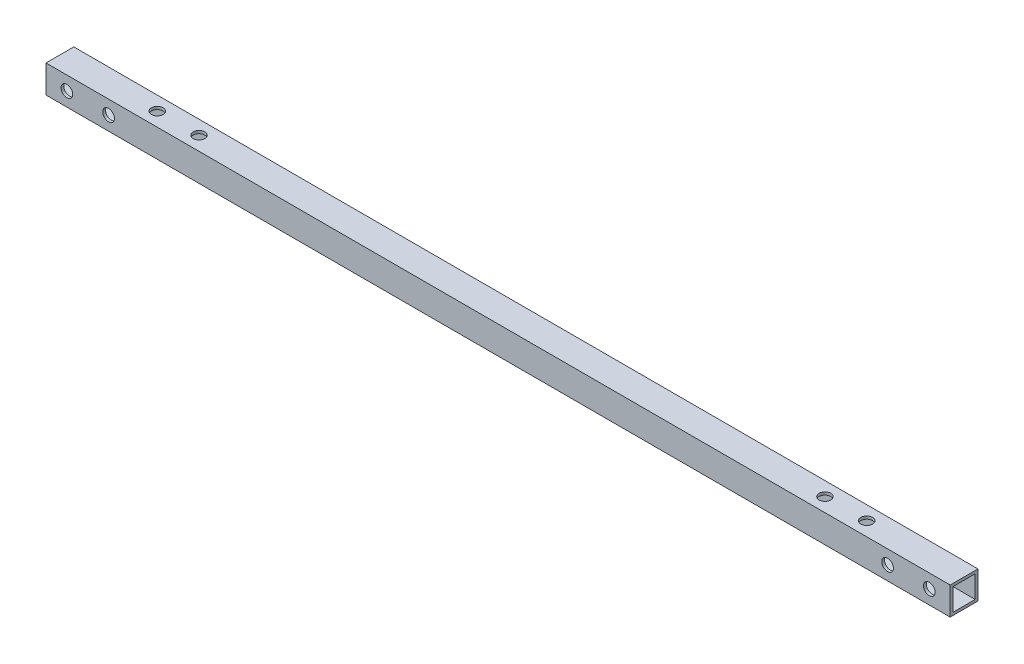
SolidWorks part; units mm, degrees
material "5052-H34"
ref_plane "正面" through (0, 0, 0) normal (0, 0, 1) x (1, 0, 0)
ref_plane "平面" through (0, 0, 0) normal (0, 1, 0) x (1, 0, 0)
ref_plane "右側面" through (0, 0, 0) normal (1, 0, 0) x (0, 0, -1)
sketch "ｽｹｯﾁ1" plane through (0, 0, 0) normal (1, 0, 0) x (0, 0, -1)
  line L1 (-5, 5) -> (5, 5)
  line L2 (-5, 5) -> (-5, -5)
  line L3 (-5, -5) -> (5, -5)
  line L4 (5, 5) -> (5, -5)
  line L5 (-5, 5) -> (5, -5) construction
  line L6 (-5, -5) -> (5, 5) construction
  point P0 (0, 0)
  dimension "D1" = 10
extrude "押し出し-薄板1" add sketch "ｽｹｯﾁ1" along normal blind 325 thin
sketch "ｽｹｯﾁ2" plane through (0, 0, 5) normal (0, 0, 1) x (1, 0, 0)
  line L0 (162.5, 5) -> (162.5, -5) construction
  line L1 (325, 5) -> (0, 5) construction
  line L2 (325, -5) -> (0, -5) construction
  line L3 (0, 0) -> (22.5, 0) construction
  circle A0 centre (22.5, 0) radius 2.1
  circle A1 centre (7.5, 0) radius 2.1
  circle A2 centre (317.5, 0) radius 2.1
  circle A3 centre (302.5, 0) radius 2.1
  dimension "D1" = 4.2
  dimension "D4" = 4.2
  dimension "D2" = 7.5
  dimension "D3" = 22.5
extrude "ｶｯﾄ - 押し出し1" cut sketch "ｽｹｯﾁ2" against normal through all
sketch "ｽｹｯﾁ3" plane through (0, 5, 0) normal (0, 1, 0) x (1, 0, 0)
  line L0 (325, 0) -> (275, 0) construction
  line L1 (325, 5) -> (325, -5) construction
  line L2 (162.5, 5) -> (162.5, -5) construction
  line L3 (325, 5) -> (0, 5) construction
  line L4 (325, -5) -> (0, -5) construction
  circle A0 centre (275, 0) radius 2.1
  circle A1 centre (290, 0) radius 2.1
  circle A2 centre (35, 0) radius 2.1
  circle A3 centre (50, 0) radius 2.1
  dimension "D1" = 4.2
  dimension "D2" = 15
  dimension "D3" = 35
extrude "ｶｯﾄ - 押し出し2" cut sketch "ｽｹｯﾁ3" against normal through all
